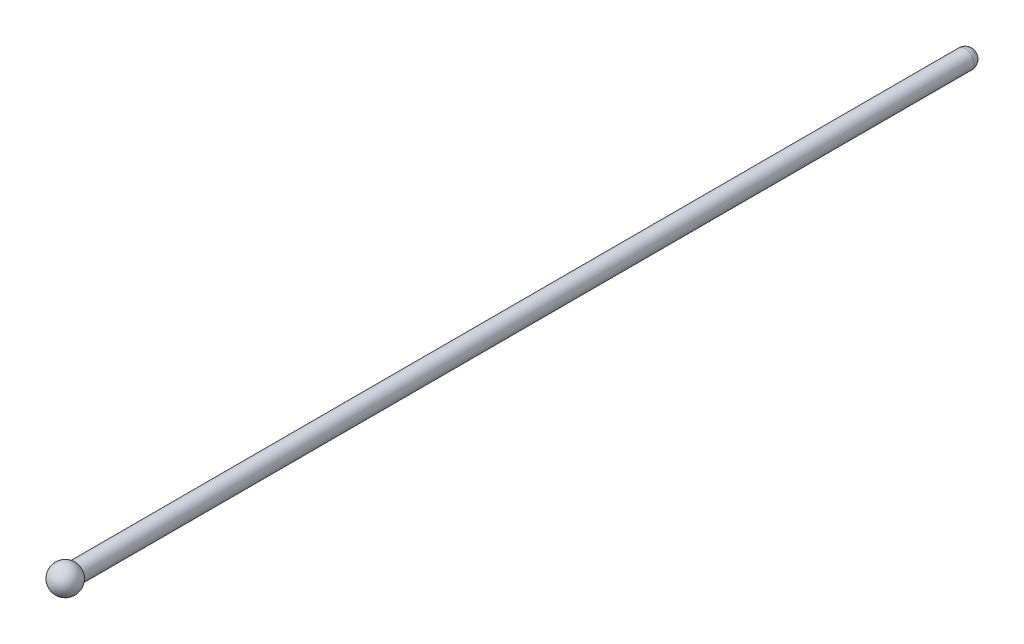
SolidWorks part; units mm, degrees
ref_plane "Front Plane" through (0, 0, 0) normal (0, 0, 1) x (1, 0, 0)
ref_plane "Top Plane" through (0, 0, 0) normal (0, 1, 0) x (1, 0, 0)
ref_plane "Right Plane" through (0, 0, 0) normal (1, 0, 0) x (0, 0, -1)
sketch "Sketch1" plane through (0, 0, 0) normal (0, 0, 1) x (1, 0, 0)
  circle A0 centre (0, 0) radius 0.5
  dimension "D1" = 1
extrude "Boss-Extrude1" add sketch "Sketch1" along normal blind 50
sketch "Sketch3" plane through (0, 0, 50) normal (0, 0, 1) x (1, 0, 0)
  line L0 (-0.75, 0) -> (0.75, 0)
  arc A0 (-0.75, 0) -> (0.75, 0) centre (0, 0) cw
  point P3 (0, 0)
  dimension "D1" = 1.5
revolve "Revolve1" add sketch "Sketch3" angle 360 about L0
fillet "Fillet2" radius 0.5 1 edges at (0.5, 0, 0)
